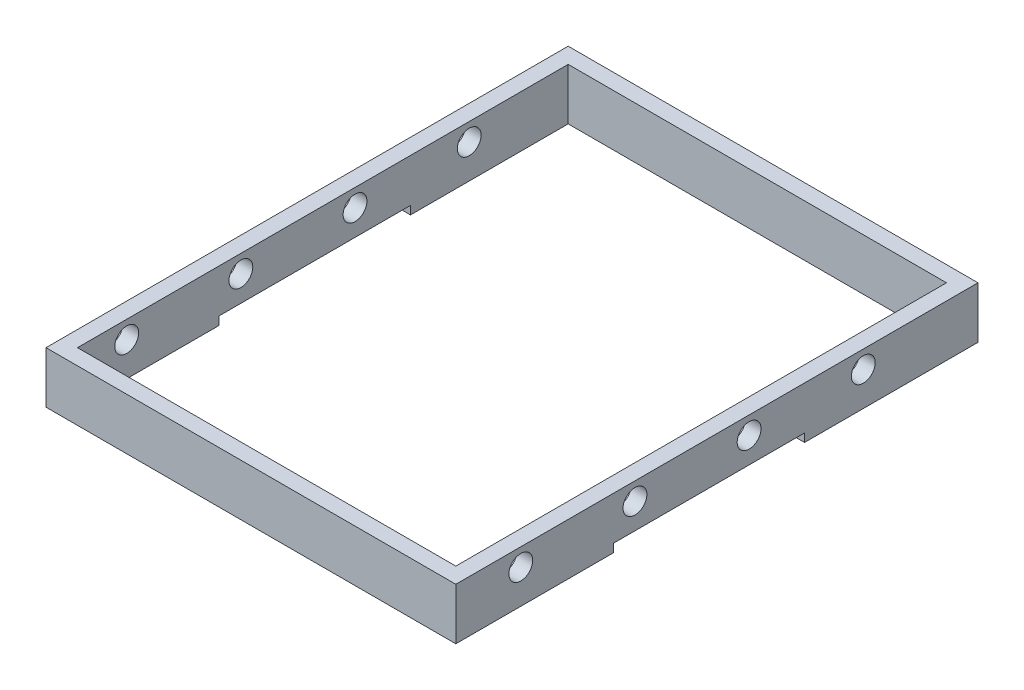
SolidWorks part; units mm, degrees
ref_plane "Front Plane" through (0, 0, 0) normal (0, 0, 1) x (1, 0, 0)
ref_plane "Top Plane" through (0, 0, 0) normal (0, 1, 0) x (1, 0, 0)
ref_plane "Right Plane" through (0, 0, 0) normal (1, 0, 0) x (0, 0, -1)
sketch "Sketch1" plane through (0, 0, 0) normal (0, 1, 0) x (1, 0, 0)
  line L1 (-48.05, -62.32) -> (48.05, -62.32)
  line L2 (-48.05, -62.32) -> (-48.05, 62.32)
  line L3 (-48.05, 62.32) -> (48.05, 62.32)
  line L4 (48.05, -62.32) -> (48.05, 62.32)
  line L5 (-48.05, -62.32) -> (48.05, 62.32) construction
  line L6 (-48.05, 62.32) -> (48.05, -62.32) construction
  line L7 (-52.05, -66.32) -> (52.05, -66.32)
  line L8 (-52.05, -66.32) -> (-52.05, 66.32)
  line L9 (-52.05, 66.32) -> (52.05, 66.32)
  line L10 (52.05, -66.32) -> (52.05, 66.32)
  line L11 (-52.05, -66.32) -> (52.05, 66.32) construction
  line L12 (-52.05, 66.32) -> (52.05, -66.32) construction
  point P0 (0, 0)
  point P6 (0, 0)
  dimension "D1" = 4
  dimension "D2" = 4
  dimension "D3" = 124.64
  dimension "D4" = 96.1
extrude "Boss-Extrude1" add sketch "Sketch1" along normal blind 11
sketch "Sketch3" plane through (52.05, 0, 0) normal (1, 0, 0) x (0, 0, -1)
  line L0 (-49.82, 6.5) -> (-62.32, 6.5) construction
  line L1 (-62.32, 11) -> (-62.32, 0) construction
  line L3 (-66.32, 11) -> (66.32, 11) construction
  circle A0 centre (-49.82, 6.5) radius 3.025
  dimension "D3" = 6.05
  dimension "D1" = 4.5
  dimension "D2" = 12.5
extrude "Cut-Extrude1" cut sketch "Sketch3" against normal through all
pattern_linear "LPattern1" count 4 spacing 29 along (0, 0, -1) of "Cut-Extrude1"
sketch "Sketch5" plane through (0, 0, 0) normal (0, -1, 0) x (1, 0, 0)
  line L0 (48.05, 62.32) -> (48.05, 26.32)
  line L1 (48.05, 62.32) -> (48.05, -62.32) construction
  line L2 (48.05, 26.32) -> (52.05, 26.32)
  line L3 (52.05, 66.32) -> (52.05, -66.32) construction
  line L4 (52.05, 26.32) -> (52.05, 66.32)
  line L5 (52.05, 66.32) -> (-52.05, 66.32)
  line L6 (-52.05, 66.32) -> (-52.05, 26.32)
  line L7 (-52.05, -66.32) -> (-52.05, 66.32) construction
  line L8 (-52.05, 26.32) -> (-48.05, 26.32)
  line L9 (-48.05, -62.32) -> (-48.05, 62.32) construction
  line L10 (-48.05, 26.32) -> (-48.05, 62.32)
  line L11 (-48.05, 62.32) -> (48.05, 62.32)
  line L12 (-48.05, -22.26) -> (-52.05, -22.26)
  line L13 (-52.05, -22.26) -> (-52.05, -66.32)
  line L14 (-52.05, -66.32) -> (52.05, -66.32)
  line L15 (52.05, -66.32) -> (52.05, -22.26)
  line L16 (52.05, -22.26) -> (48.05, -22.26)
  line L17 (48.05, -22.26) -> (48.05, -62.32)
  line L18 (48.05, -62.32) -> (-48.05, -62.32)
  line L19 (-48.05, -62.32) -> (-48.05, -22.26)
  dimension "D1" = 36
  dimension "D2" = 48.58
extrude "Boss-Extrude2" add sketch "Sketch5" along normal blind 2.1
